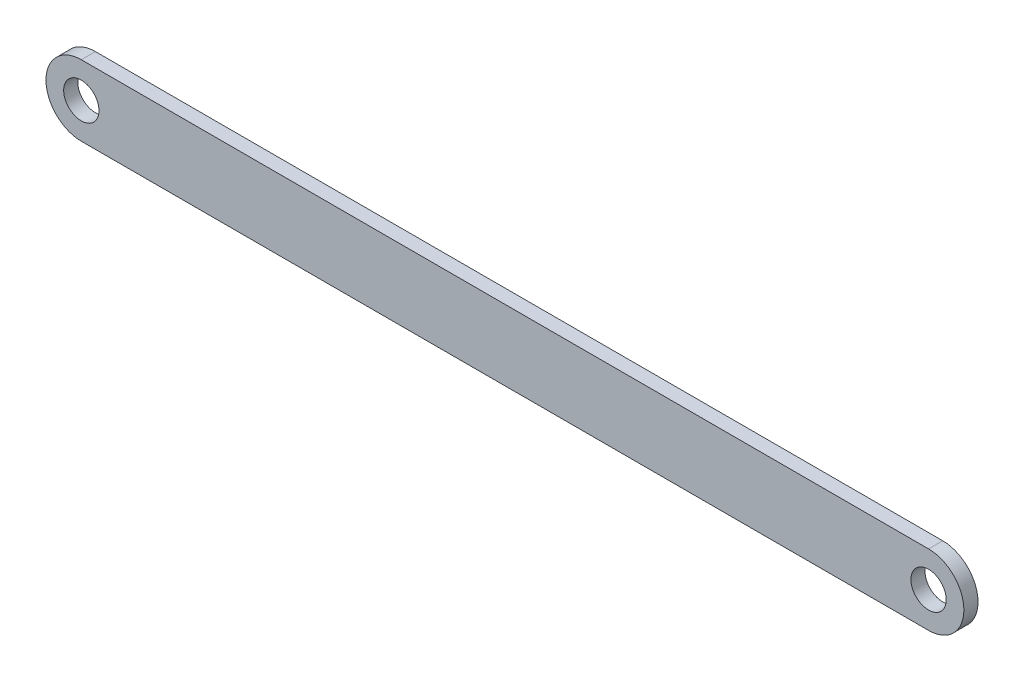
SolidWorks part; units mm, degrees
material "AISI 1020"
ref_plane "Front Plane" through (0, 0, 0) normal (0, 0, 1) x (1, 0, 0)
ref_plane "Top Plane" through (0, 0, 0) normal (0, 1, 0) x (1, 0, 0)
ref_plane "Right Plane" through (0, 0, 0) normal (1, 0, 0) x (0, 0, -1)
sketch "Sketch1" plane through (0, 0, 0) normal (0, 0, 1) x (1, 0, 0)
  line L0 (98.1361, 0) -> (0, 0) construction
  line L1 (0, 0) -> (0, 72.9865) construction
  line L2 (-76.2, 6.35) -> (76.2, 6.35)
  line L3 (-76.2, -6.35) -> (76.2, -6.35)
  arc A0 (76.2, 6.35) -> (76.2, -6.35) centre (76.2, 0) cw
  arc A1 (-76.2, 6.35) -> (-76.2, -6.35) centre (-76.2, 0) ccw
  circle A2 centre (-76.2, 0) radius 3.175
  circle A3 centre (76.2, 0) radius 3.175
  point P7 (0, 6.35)
  point P13 (0, -6.35)
  dimension "D2" = 6.35
  dimension "D3" = 6.35
  dimension "D1" = 152.4
extrude "Boss-Extrude1" add sketch "Sketch1" along normal blind 2.54
